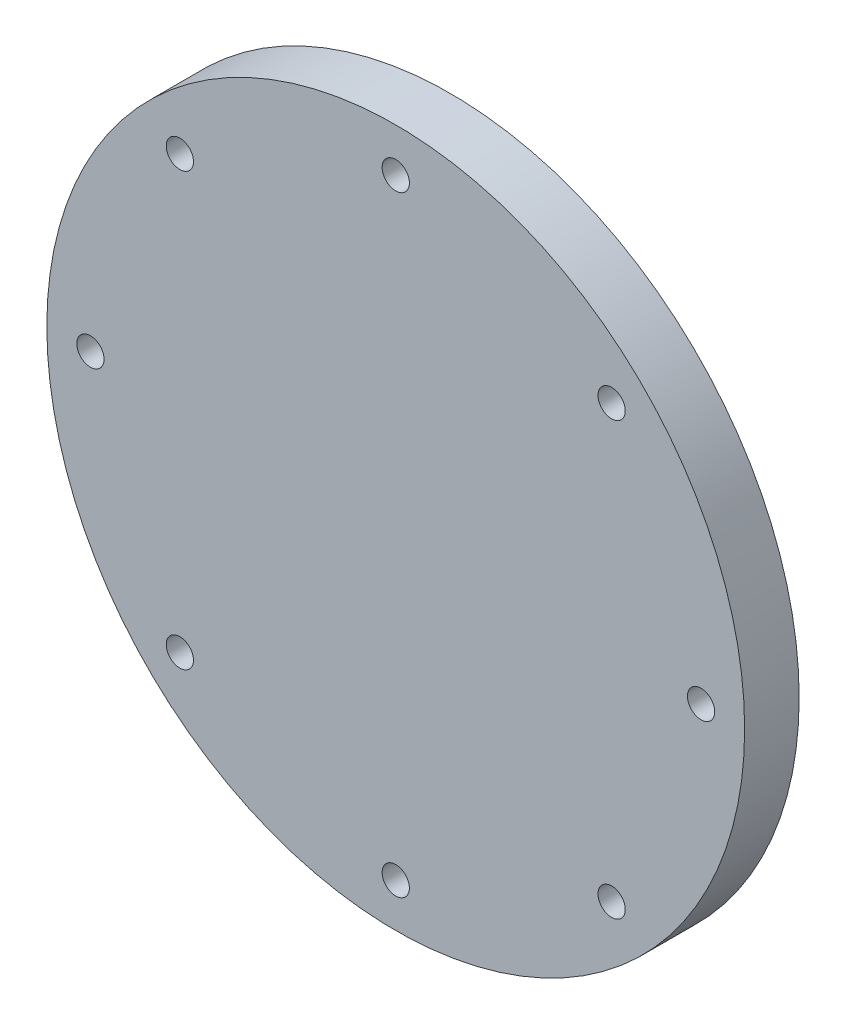
SolidWorks part; units mm, degrees
ref_plane "Alzado" through (0, 0, 0) normal (0, 0, 1) x (1, 0, 0)
ref_plane "Planta" through (0, 0, 0) normal (0, 1, 0) x (1, 0, 0)
ref_plane "Vista lateral" through (0, 0, 0) normal (1, 0, 0) x (0, 0, -1)
sketch "Croquis1" plane through (0, 0, 0) normal (0, 0, 1) x (1, 0, 0)
  circle A0 centre (0, 0) radius 32
  dimension "D1" = 64
extrude "Saliente-Extruir1" add sketch "Croquis1" along normal blind 5
sketch "Croquis2" plane through (0, 0, 5) normal (0, 0, 1) x (1, 0, 0)
  line L0 (0, 0) -> (0, 28) construction
  line L1 (0, 0) -> (19.799, 19.799) construction
  line L2 (0, 0) -> (28, 0) construction
  line L3 (0, 0) -> (19.799, -19.799) construction
  line L4 (0, 0) -> (0, -28) construction
  line L5 (0, 0) -> (-19.799, -19.799) construction
  line L6 (0, 0) -> (-28, 0) construction
  line L7 (0, 0) -> (-19.799, 19.799) construction
  circle A0 centre (0, 28) radius 1.25
  circle A1 centre (0, 0) radius 32 construction
  circle A2 centre (19.799, 19.799) radius 1.25
  circle A3 centre (28, 0) radius 1.25
  circle A4 centre (19.799, -19.799) radius 1.25
  circle A5 centre (0, -28) radius 1.25
  circle A6 centre (-19.799, -19.799) radius 1.25
  circle A7 centre (-28, 0) radius 1.25
  circle A8 centre (-19.799, 19.799) radius 1.25
  point P19 (0, 0)
  dimension "D1" = 2.5
  dimension "D2" = 28
  dimension "D3" = 8
extrude "Cortar-Extruir1" cut sketch "Croquis2" against normal through all
